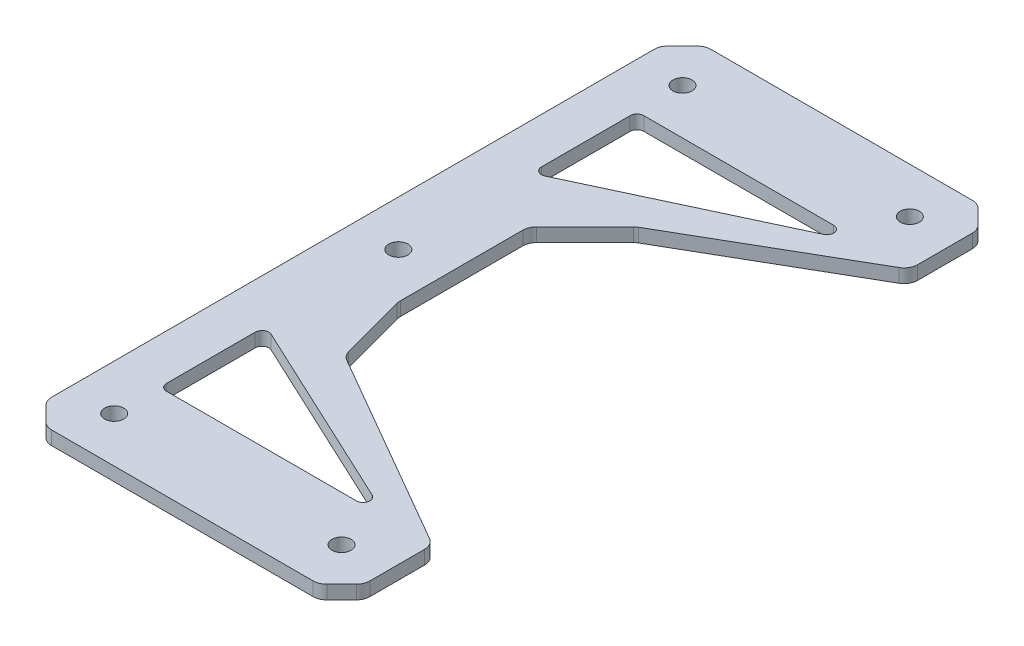
SolidWorks part; units mm, degrees
material "A-玻璃纤维"
ref_plane "前视基准面" through (0, 0, 0) normal (0, 0, 1) x (1, 0, 0)
ref_plane "上视基准面" through (0, 0, 0) normal (0, 1, 0) x (1, 0, 0)
ref_plane "右视基准面" through (0, 0, 0) normal (1, 0, 0) x (0, 0, -1)
sketch "草图1" plane through (0, 0, 0) normal (0, 1, 0) x (1, 0, 0)
  line L0 (0, 0) -> (54.0903, 0) construction
  line L1 (0, 62.5) -> (0, -62.5) construction
  line L2 (0, 62.5) -> (60, 62.5) construction
  line L3 (0, -62.5) -> (60, -62.5) construction
  line L4 (10, -52.5) -> (60, -52.5)
  line L5 (10, 52.5) -> (10, -52.5)
  line L6 (10, 52.5) -> (60, 52.5)
  line L7 (-10, -72.5) -> (60, -72.5)
  line L8 (-10, 72.5) -> (-10, -72.5)
  line L9 (-10, 72.5) -> (60, 72.5)
  line L10 (60, 72.5) -> (60, 52.5)
  line L11 (60, -52.5) -> (60, -72.5)
  line L12 (60, 52.5) -> (10, 23.6325)
  line L13 (60, -52.5) -> (10, -23.6325)
  circle A0 centre (0, 62.5) radius 2.1
  circle A1 centre (50, 62.5) radius 2.1
  circle A2 centre (0, 0) radius 2.1
  circle A3 centre (50, -62.5) radius 2.1
  circle A4 centre (0, -62.5) radius 2.1
  dimension "D1" = 4.2
  dimension "D2" = 50
  dimension "D3" = 62.5
  dimension "D6" = 10
  dimension "D7" = 30
  dimension "D4" = 10
  dimension "D5" = 10
extrude "凸台-拉伸1" add sketch "草图1" along normal blind 3 contours L12 L6 L5 | L4 L13 L5 | L11 L4 L5 L6 L10 L9 L8 L7 A3 A2 A1 A0 A4
chamfer "倒角1" distance 5 angle 45 6 edges at (60, 1.5, 72.5) (-10, 1.5, 72.5) (10, 1.5, 23.6325) (10, 1.5, -23.6325) (60, 1.5, -72.5) (-10, 1.5, -72.5)
fillet "圆角1" radius 3 14 edges at (60, 1.5, 52.5) (14.3301, 1.5, 26.1325) (10, 1.5, 9.9722) (10, 1.5, -18.6325) (21.8301, 1.5, -30.4626) (60, 1.5, -52.5) (60, 1.5, -67.5) (55, 1.5, -72.5) (-5, 1.5, -72.5) (-10, 1.5, -67.5) (-10, 1.5, 67.5) (-5, 1.5, 72.5) (60, 1.5, 67.5) (55, 1.5, 72.5)
sketch "草图3" plane through (0, 3, 0) normal (0, 1, 0) x (1, 0, 0)
  line L0 (0, 52.5) -> (50, 52.5)
  line L1 (0, 52.5) -> (0, 29.1261)
  line L2 (0, 29.1261) -> (50, 52.5)
  line L3 (0, 0) -> (50, 0) construction
  line L4 (0, -29.1261) -> (50, -52.5)
  line L5 (0, -52.5) -> (0, -29.1261)
  line L6 (0, -52.5) -> (50, -52.5)
  circle A0 centre (0, 62.5) radius 10
  circle A1 centre (50, 62.5) radius 10
  circle A2 centre (0, 0) radius 10
  circle A3 centre (0, -62.5) radius 10
  circle A4 centre (50, -62.5) radius 10
  dimension "D1" = 20
  dimension "D2" = 8
extrude "切除-拉伸1" cut sketch "草图3" against normal blind 10 contours L5 L6 L4 | L1 L2 L0
fillet "圆角2" radius 1.5 6 edges at (50, 1.5, 52.5) (0, 1.5, 52.5) (0, 1.5, 29.1261) (50, 1.5, -52.5) (0, 1.5, -29.1261) (0, 1.5, -52.5)
